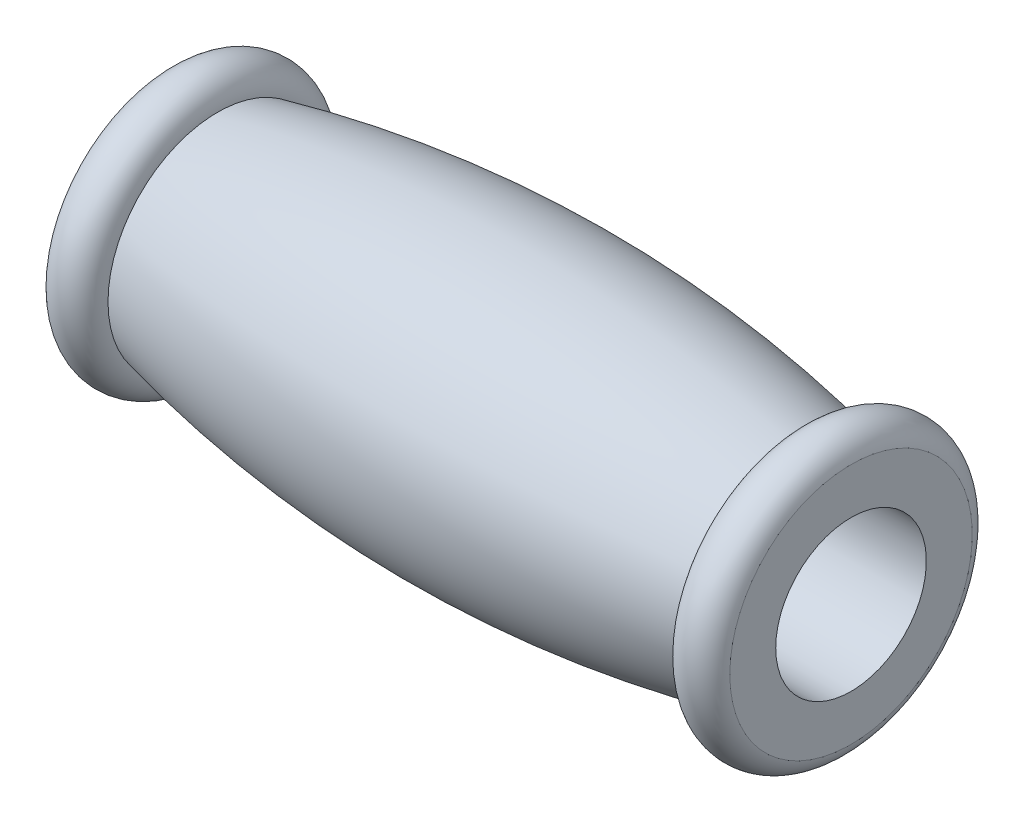
SolidWorks part; units mm, degrees
ref_plane "Front Plane" through (0, 0, 0) normal (0, 0, 1) x (1, 0, 0)
ref_plane "Top Plane" through (0, 0, 0) normal (0, 1, 0) x (1, 0, 0)
ref_plane "Right Plane" through (0, 0, 0) normal (1, 0, 0) x (0, 0, -1)
sketch "Sketch1" plane through (0, 0, 0) normal (0, 0, 1) x (1, 0, 0)
  line L0 (-100, 0) -> (119.2913, 0) construction
  line L1 (-50, 11) -> (50, 11)
  line L2 (0, 0) -> (0, 11) construction
  line L4 (-50, 11) -> (-50, 16)
  line L7 (50, 11) -> (50, 17.7)
  arc A0 (-42.5, 16) -> (-50, 16) centre (-46.25, 16) ccw
  arc A1 (-42.5, 16) -> (42.5, 16) centre (0, -168.5943) cw
  arc A2 (50, 17.7) -> (42.5, 16) centre (46.25, 16.85) ccw
  point P5 (0, 11)
  point P11 (0, 17.7)
  dimension "D1" = 100
  dimension "D2" = 85
  dimension "D4" = 11
revolve "Revolve1" add sketch "Sketch1" angle 360 about L0
